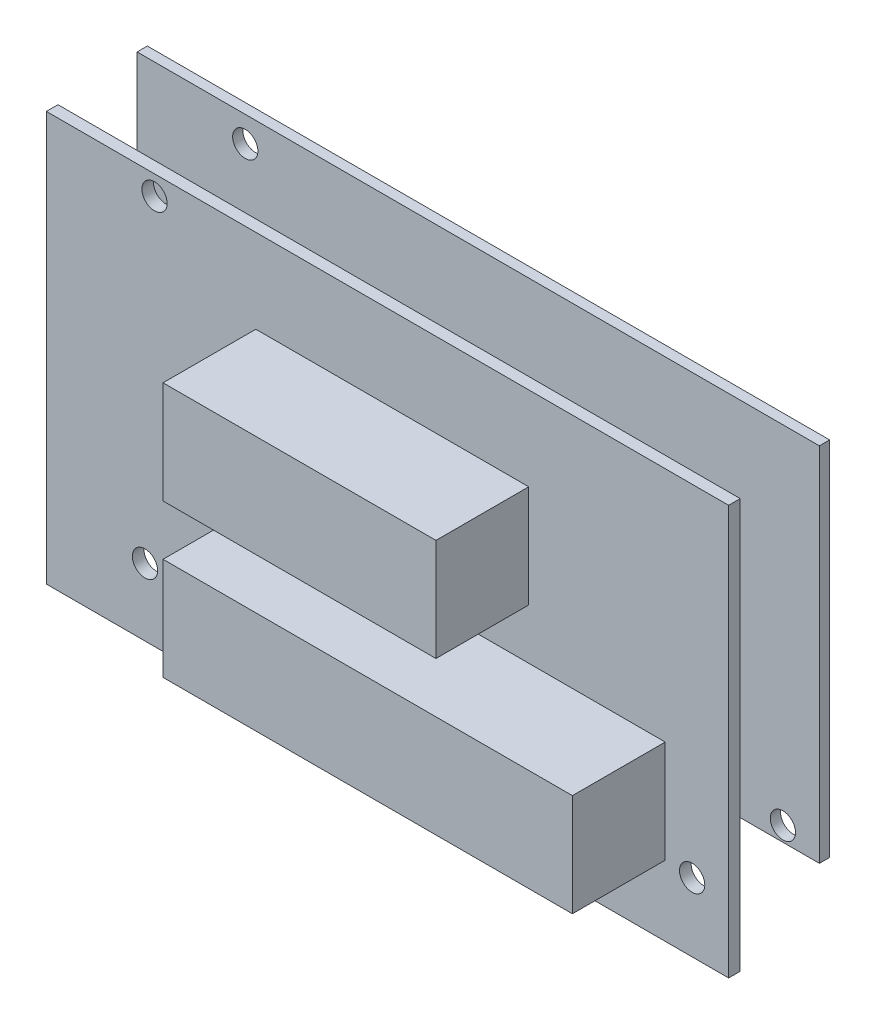
SolidWorks part; units mm, degrees
ref_plane "Plano frontal" through (0, 0, 0) normal (0, 0, 1) x (1, 0, 0)
ref_plane "Plano superior" through (0, 0, 0) normal (0, 1, 0) x (1, 0, 0)
ref_plane "Plano direito" through (0, 0, 0) normal (1, 0, 0) x (0, 0, -1)
sketch "Esboço1" plane through (0, 0, 0) normal (0, 0, 1) x (1, 0, 0)
  line L1 (-50, 30) -> (50, 30)
  line L2 (-50, 30) -> (-50, -30)
  line L3 (-50, -30) -> (50, -30)
  line L4 (50, 30) -> (50, -30)
  line L5 (-50, 30) -> (50, -30) construction
  line L6 (-50, -30) -> (50, 30) construction
  circle A0 centre (-34.15, 27.15) radius 1.85
  circle A1 centre (-35.55, -20.15) radius 1.85
  circle A2 centre (44.65, -19.95) radius 1.85
  point P0 (0, 0)
  dimension "D3" = 1
  dimension "D4" = 3.7
  dimension "D5" = 14
  dimension "D6" = 12.6
  dimension "D7" = 8
  dimension "D8" = 3.5
  dimension "D9" = 8.2
  dimension "D1" = 60
  dimension "D2" = 100
extrude "Ressalto-extrusão1" add sketch "Esboço1" along normal blind 1.7
sketch "Esboço2" plane through (0, 0, 1.7) normal (0, 0, 1) x (1, 0, 0)
  line L0 (-50, -30) -> (50, -30) construction
  line L1 (-19.3, -4.7) -> (40.7, -4.7)
  line L2 (-19.3, -4.7) -> (-19.3, -19.7)
  line L3 (-19.3, -19.7) -> (40.7, -19.7)
  line L4 (40.7, -4.7) -> (40.7, -19.7)
  line L5 (50, -30) -> (50, 30) construction
  line L7 (-19.3, 2.7) -> (20.7, 2.7)
  line L8 (-19.3, 2.7) -> (-19.3, 17.7)
  line L9 (-19.3, 17.7) -> (20.7, 17.7)
  line L10 (20.7, 2.7) -> (20.7, 17.7)
  dimension "D1" = 60
  dimension "D2" = 15
  dimension "D3" = 10.3
  dimension "D4" = 9.3
  dimension "D5" = 40
  dimension "D6" = 7.4
extrude "Ressalto-extrusão2" add sketch "Esboço2" along normal blind 13.6
sketch "Esboço3" plane through (0, 0, 0) normal (0, 0, -1) x (-1, 0, 0)
  line L0 (50, -30) -> (-50, -30) construction
  line L1 (50, 30.9) -> (-50, 30.9)
  line L2 (50, 30.9) -> (50, -22.1)
  line L3 (50, -22.1) -> (-50, -22.1)
  line L4 (-50, 30.9) -> (-50, -22.1)
  line L5 (50, 30) -> (50, -30) construction
  line L6 (-50, -30) -> (-50, 30) construction
  circle A0 centre (-44.65, -19.95) radius 1.85 construction
  circle A1 centre (34.15, 27.15) radius 1.85 construction
  circle A2 centre (35.55, -20.15) radius 1.85 construction
  circle A3 centre (-44.65, -19.95) radius 1.85
  circle A4 centre (34.15, 27.15) radius 1.85
  circle A5 centre (35.55, -20.15) radius 1.85
  point P7 (50, 25.5801)
  point P10 (0, 0)
  dimension "D1" = 7.9
  dimension "D2" = 53
extrude "Ressalto-extrusão6" add sketch "Esboço3" along normal blind 1.5 from offset 11.6 separate body
equation "\"D5@Esboço2\"=\"D1@Esboço2\"*2/3"
